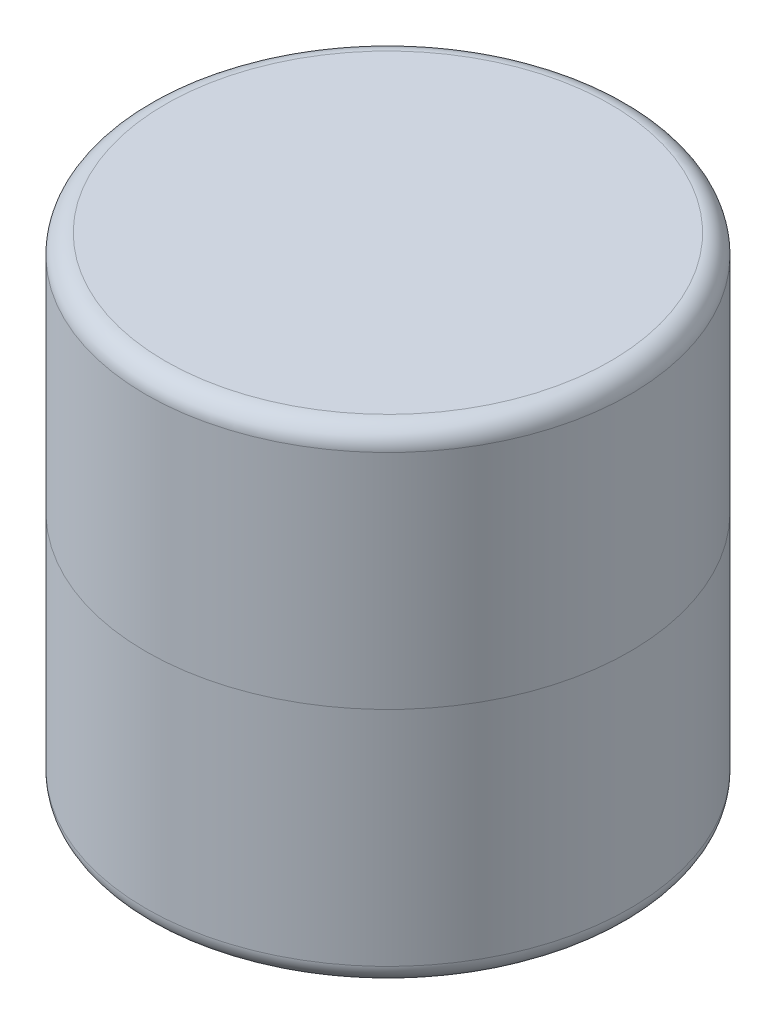
SolidWorks part; units mm, degrees
ref_plane "Front Plane" through (0, 0, 0) normal (0, 0, 1) x (1, 0, 0)
ref_plane "Top Plane" through (0, 0, 0) normal (0, 1, 0) x (1, 0, 0)
ref_plane "Right Plane" through (0, 0, 0) normal (1, 0, 0) x (0, 0, -1)
sketch "Sketch1" plane through (0, 0, 0) normal (0, 1, 0) x (1, 0, 0)
  circle A0 centre (0, 0) radius 2.5
  dimension "D1" = 5
extrude "Boss-Extrude1" add sketch "Sketch1" along normal blind 2.5
fillet "Fillet1" radius 0.2 1 edges at (0, 0, 2.5)
ref_plane "Plane1" through (0, 2.5, 0) normal (0, 1, 0) x (1, 0, 0)
mirror "Mirror1" about plane through (0, 2.5, 0) normal (0, 1, 0) of bodies 101
